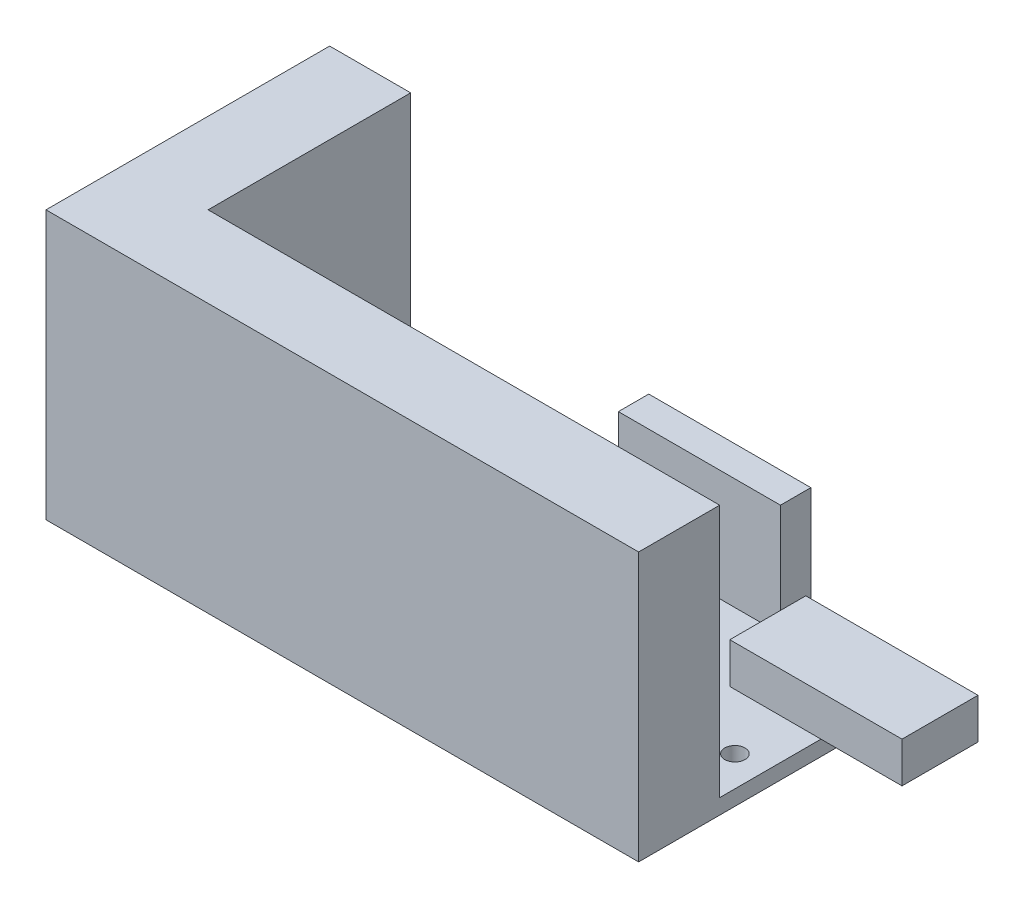
SolidWorks part; units mm, degrees
ref_plane "Спереди" through (0, 0, 0) normal (0, 0, 1) x (1, 0, 0)
ref_plane "Сверху" through (0, 0, 0) normal (0, 1, 0) x (1, 0, 0)
ref_plane "Справа" through (0, 0, 0) normal (1, 0, 0) x (0, 0, -1)
sketch "Эскиз1" plane through (0, 0, 0) normal (0, 1, 0) x (1, 0, 0)
  line L0 (0, 0) -> (-58.5, 0)
  line L1 (-58.5, 0) -> (-58.5, 28)
  line L2 (-58.5, 28) -> (0, 28)
  line L3 (0, 28) -> (0, 0)
extrude "Бобышка-Вытянуть1" add sketch "Эскиз1" along normal blind 1.5
sketch "Эскиз2" plane through (0, 1.5, 0) normal (0, 1, 0) x (1, 0, 0)
  line L0 (0, 0) -> (0, 12.5) construction
  line L1 (0, 0) -> (0, 28) construction
  line L2 (0, 12.5) -> (-3, 12.5) construction
  line L3 (-58.5, 28) -> (-41.5, 28) construction
  line L4 (0, 28) -> (-58.5, 28) construction
  line L5 (-41.5, 28) -> (-41.5, 25.5) construction
  circle A0 centre (-3, 12.5) radius 1
  circle A1 centre (-41.5, 25.5) radius 1
  dimension "D1" = 12.5
  dimension "D3" = 17
  dimension "D2" = 3
  dimension "D4" = 2.5
extrude "Вырез-Вытянуть1" cut sketch "Эскиз2" against normal blind 1.5
sketch "Эскиз3" plane through (0, 1.5, 0) normal (0, 1, 0) x (1, 0, 0)
  line L0 (0, 0) -> (0, 8)
  line L1 (0, 0) -> (0, 28) construction
  line L2 (0, 8) -> (-50.5, 8)
  line L3 (-58.5, 28) -> (-58.5, 0) construction
  line L4 (-58.5, 28) -> (-50.5, 28)
  line L5 (0, 28) -> (-58.5, 28) construction
  line L6 (-50.5, 28) -> (-50.5, 8)
  line L7 (-58.5, 0) -> (-58.5, 28)
  line L8 (-58.5, 0) -> (0, 0)
extrude "Бобышка-Вытянуть2" add sketch "Эскиз3" along normal blind 25
sketch "Эскиз4" plane through (0, 1.5, 0) normal (0, 1, 0) x (1, 0, 0)
  line L0 (-11, 28) -> (-27, 28)
  line L1 (0, 28) -> (-50.5, 28) construction
  line L2 (-27, 28) -> (-11, 28)
  line L3 (-11, 28) -> (-11, 25)
  line L4 (-11, 25) -> (-27, 25)
  line L5 (-27, 25) -> (-27, 28)
  line M6 (0, 28) -> (-50.5, 28)
extrude "Бобышка-Вытянуть3" add sketch "Эскиз4" along normal blind 11 contours L5 L4 L3 M6
sketch "Эскиз5" plane through (0, 1.5, 0) normal (0, 1, 0) x (1, 0, 0)
  line L0 (0, 28) -> (0, 18)
  line L1 (0, 8) -> (0, 28) construction
  line L2 (0, 18) -> (-9, 18)
  line L3 (-9, 18) -> (-9, 25.5)
  line L4 (-9, 25.5) -> (8, 25.5)
  line L5 (8, 25.5) -> (8, 18)
  line L6 (8, 18) -> (0, 18)
  line M8 (0, 8) -> (0, 28)
extrude "Бобышка-Вытянуть4" add sketch "Эскиз5" along normal blind 4 contours L6 L5 L4 M8 | L4 L3 L2 M8
